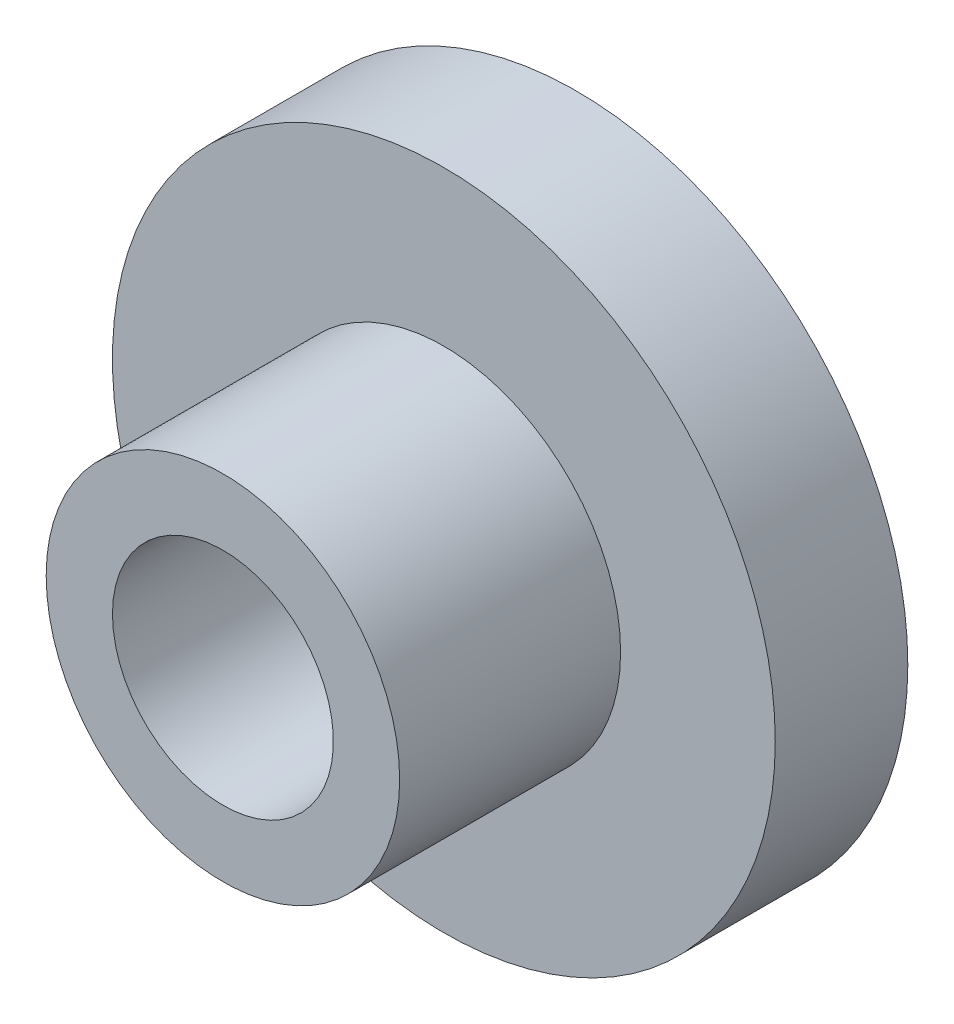
SolidWorks part; units mm, degrees
material "Zero density"
ref_plane "Piano frontale" through (0, 0, 0) normal (0, 0, 1) x (1, 0, 0)
ref_plane "Piano superiore" through (0, 0, 0) normal (0, 1, 0) x (1, 0, 0)
ref_plane "Piano destro" through (0, 0, 0) normal (1, 0, 0) x (0, 0, -1)
sketch "Schizzo1" plane through (0, 0, 0) normal (0, 0, 1) x (1, 0, 0)
  circle A0 centre (0, 0) radius 7.5
  dimension "D1" = 15
extrude "Estrusione-Estrusione1" add sketch "Schizzo1" along normal blind 3
sketch "Schizzo2" plane through (0, 0, 3) normal (0, 0, 1) x (1, 0, 0)
  circle A0 centre (0, 0) radius 4
  dimension "D1" = 8
extrude "Estrusione-Estrusione2" add sketch "Schizzo2" along normal blind 5
sketch "Schizzo3" plane through (0, 0, 0) normal (0, 0, -1) x (-1, 0, 0)
  circle A0 centre (0, 0) radius 2.5
  dimension "D1" = 5
extrude "Taglio-Estrusione1" cut sketch "Schizzo3" against normal through all
